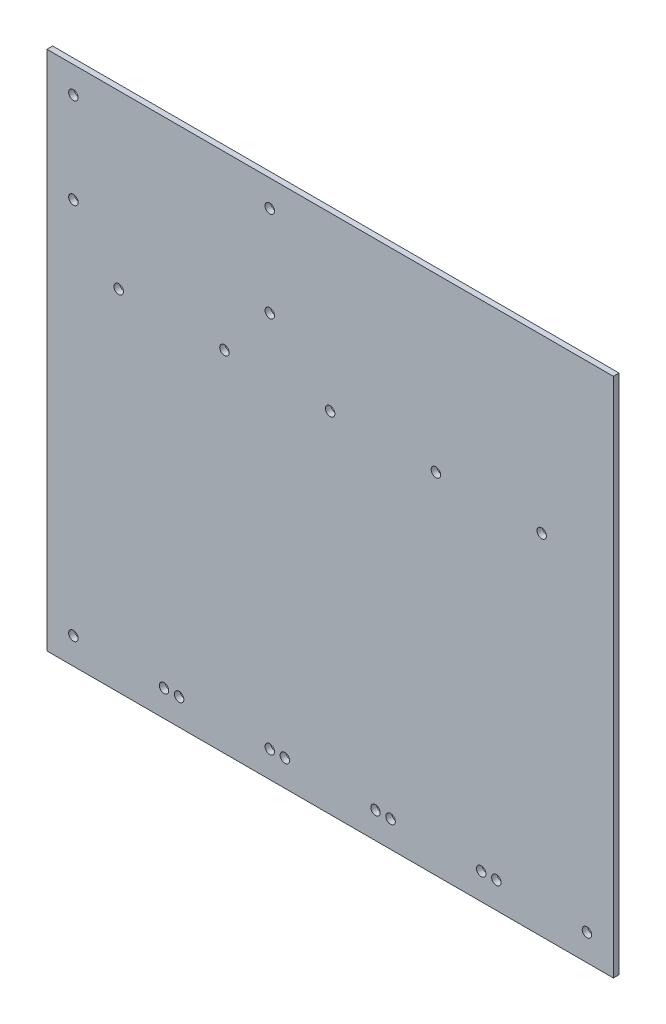
SolidWorks part; units mm, degrees
ref_plane "Front Plane" through (0, 0, 0) normal (0, 0, 1) x (1, 0, 0)
ref_plane "Top Plane" through (0, 0, 0) normal (0, 1, 0) x (1, 0, 0)
ref_plane "Right Plane" through (0, 0, 0) normal (1, 0, 0) x (0, 0, -1)
sketch "Sketch1" plane through (0, 0, 0) normal (0, 0, 1) x (1, 0, 0)
  line L1 (-112, 200) -> (168, 200)
  line L2 (-112, 200) -> (-112, 0)
  line L3 (-112, 0) -> (168, 0)
  line L4 (168, 200) -> (168, 0)
  circle A0 centre (-108, 4) radius 2.5
  circle A1 centre (-60, 4) radius 2.5
  circle A2 centre (-52, 4) radius 2.5
  circle A3 centre (-4, 4) radius 2.5
  circle A4 centre (4, 4) radius 2.5
  circle A5 centre (52, 4) radius 2.5
  circle A6 centre (60, 4) radius 2.5
  circle A7 centre (108, 4) radius 2.5
  circle A8 centre (116, 4) radius 2.5
  circle A9 centre (164, 4) radius 2.5
  circle A10 centre (140, 175) radius 2.5
  circle A11 centre (84, 175) radius 2.5
  circle A12 centre (28, 175) radius 2.5
  circle A13 centre (-28, 175) radius 2.5
  circle A14 centre (-84, 175) radius 2.5
extrude "Boss-Extrude1" add sketch "Sketch1" along normal blind 3
sketch "Sketch3" plane through (0, 0, 3) normal (0, 0, 1) x (1, 0, 0)
  line L0 (168, 200) -> (178, 200)
  line L1 (-112, 200) -> (-122, 200)
  line L2 (-112, 200) -> (-112, 0)
  line L3 (-112, 0) -> (-122, 0)
  line L4 (-122, 200) -> (-122, 0)
  line L5 (178, 200) -> (178, 0)
  line L6 (178, 0) -> (168, 0)
  line M12 (-112, 200) -> (-112, 0)
  line M14 (168, 0) -> (168, 200)
extrude "Boss-Extrude2" add sketch "Sketch3" against normal blind 3 contours L1 L4 L3 M12 | L6 L5 L0 M14
sketch "Sketch4" plane through (0, 0, 3) normal (0, 0, 1) x (1, 0, 0)
  line L0 (-122, 0) -> (-122, -10)
  line L1 (-122, -10) -> (178, -10)
  line L2 (178, -10) -> (178, 0)
  line L3 (178, 0) -> (-122, 0)
extrude "Boss-Extrude3" add sketch "Sketch4" against normal blind 3
sketch "Sketch5" plane through (0, 0, 3) normal (0, 0, 1) x (1, 0, 0)
  line L0 (178, 200) -> (-122, 200)
  line L1 (178, 200) -> (178, 266)
  line L2 (-122, 200) -> (-122, 266)
  line L3 (178, 266) -> (-122, 266)
  circle A0 centre (-4, 204) radius 2.5
  circle A1 centre (-4, 252) radius 2.5
  circle A2 centre (-108, 252) radius 2.5
  circle A3 centre (-108, 204) radius 2.5
extrude "Boss-Extrude4" add sketch "Sketch5" against normal blind 3
